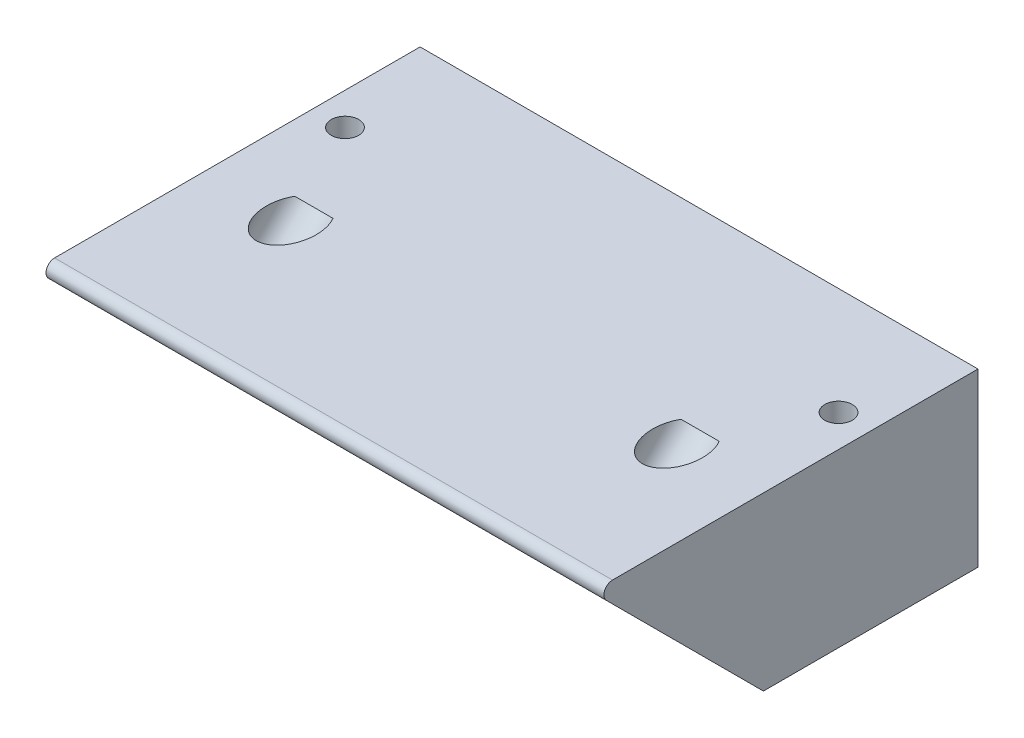
SolidWorks part; units mm, degrees
ref_plane "前视基准面" through (0, 0, 0) normal (0, 0, 1) x (1, 0, 0)
ref_plane "上视基准面" through (0, 0, 0) normal (0, 1, 0) x (1, 0, 0)
ref_plane "右视基准面" through (0, 0, 0) normal (1, 0, 0) x (0, 0, -1)
other "Configuration Table"
sketch "草图1" plane through (0, 0, 0) normal (0, 1, 0) x (1, 0, 0)
  line L1 (-32.5, -12.5) -> (32.5, -12.5)
  line L2 (-32.5, -12.5) -> (-32.5, 12.5)
  line L3 (-32.5, 12.5) -> (32.5, 12.5)
  line L4 (32.5, -12.5) -> (32.5, 12.5)
  line L5 (-32.5, -12.5) -> (32.5, 12.5) construction
  line L6 (-32.5, 12.5) -> (32.5, -12.5) construction
  point P0 (0, 0)
  dimension "D1" = 25
  dimension "D2" = 65
extrude "凸台-拉伸1" add sketch "草图1" along normal blind 20
sketch "草图2" plane through (32.5, 0, 0) normal (1, 0, 0) x (0, 0, -1)
  line L0 (-12.5, 0) -> (-32.5, 20)
  line L1 (-32.5, 20) -> (-12.5, 20)
  line L2 (-12.5, 20) -> (12.5, 20) construction
  line L3 (-12.5, 0) -> (-12.5, 20)
  dimension "D1" = 45
extrude "凸台-拉伸2" add sketch "草图2" against normal up to surface (65 mm away) up to face at (-32.5, 10, 0)
sketch "草图3" plane through (0, 0, 0) normal (0, -1, 0) x (1, 0, 0)
  line L0 (32.5, -12.5) -> (-32.5, -12.5) construction
  line L1 (-25, -12.5) -> (25, -12.5)
  line L2 (-25, -12.5) -> (-25, 7.5)
  line L3 (-25, 7.5) -> (25, 7.5)
  line L4 (25, -12.5) -> (25, 7.5)
  line L5 (0, 12.5) -> (0, -12.5) construction
  line L8 (-32.5, 12.5) -> (32.5, 12.5) construction
  dimension "D1" = 50
  dimension "D2" = 5
extrude "切除-拉伸1" cut sketch "草图3" against normal blind 15
sketch "草图4" plane through (0, -6.25, 6.25) normal (0, -0.7071, 0.7071) x (1, 0, 0)
  line L0 (0, 37.1231) -> (0, 8.8388) construction
  line L1 (-32.5, 37.1231) -> (32.5, 37.1231) construction
  line L2 (-32.5, 8.8388) -> (32.5, 8.8388) construction
  line L3 (-32.5, 22.981) -> (32.5, 22.981) construction
  line L4 (-32.5, 8.8388) -> (-32.5, 37.1231) construction
  line L5 (32.5, 37.1231) -> (32.5, 8.8388) construction
  circle A0 centre (-22.5, 22.981) radius 1.6
  circle A1 centre (22.5, 22.981) radius 1.6
  dimension "D1" = 3.2
  dimension "D2" = 45
extrude "切除-拉伸2" cut sketch "草图4" against normal through all both and the other way through all
sketch "草图5" plane through (0, -6.25, 6.25) normal (0, -0.7071, 0.7071) x (1, 0, 0)
  line L0 (0, 8.8388) -> (0, 37.1231) construction
  line L1 (-32.5, 8.8388) -> (32.5, 8.8388) construction
  line L2 (-32.5, 37.1231) -> (32.5, 37.1231) construction
  circle A0 centre (-22.5, 22.981) radius 2.9
  circle A1 centre (22.5, 22.981) radius 2.9
  dimension "D1" = 5.8
extrude "切除-拉伸3" cut sketch "草图5" against normal blind 9 from offset 7 offset against normal yes
sketch "草图6" plane through (0, 0, 0) normal (0, -1, 0) x (1, 0, 0)
  line L0 (-32.5, 0) -> (32.5, 0) construction
  line L1 (-32.5, -12.5) -> (-32.5, 12.5) construction
  line L2 (32.5, 12.5) -> (32.5, -12.5) construction
  line L3 (-28.75, -12.5) -> (-28.75, 12.5) construction
  line L4 (-25, -12.5) -> (-32.5, -12.5) construction
  line L5 (-32.5, 12.5) -> (32.5, 12.5) construction
  line L6 (28.75, -12.5) -> (28.75, 12.5) construction
  line L7 (32.5, -12.5) -> (25, -12.5) construction
  line L8 (0, -12.5) -> (0, 12.5) construction
  line L9 (-25, -12.5) -> (25, -12.5) construction
  circle A0 centre (-28.75, 7.5) radius 1.6 construction
  circle A1 centre (-28.75, 0) radius 1.6
  circle A2 centre (28.75, 0) radius 1.6
  dimension "D1" = 3.2
  dimension "D2" = 15
  dimension "D3" = 3.2
extrude "切除-拉伸4" cut sketch "草图6" against normal through all both and the other way through all
fillet "圆角1" radius 1 1 edges at (0, 20, 32.5)
